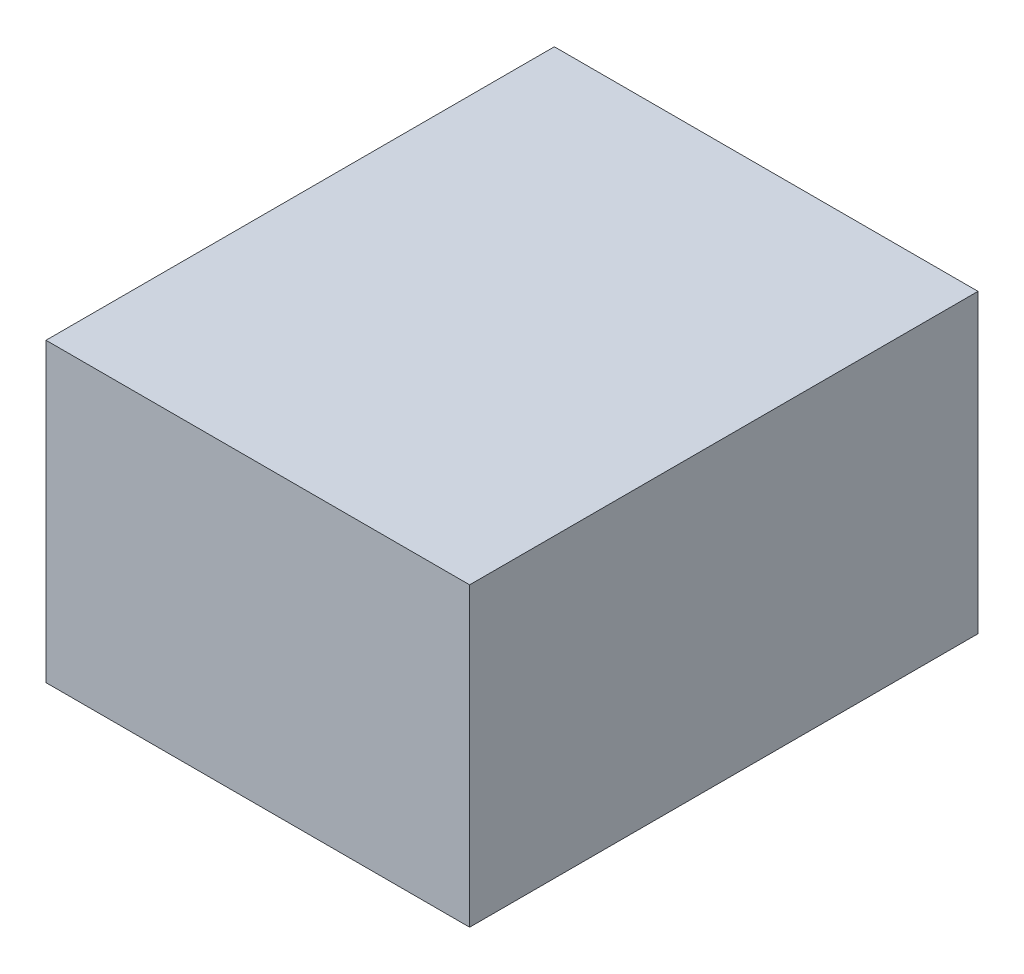
SolidWorks part; units mm, degrees
ref_plane "Front Plane" through (0, 0, 0) normal (0, 0, 1) x (1, 0, 0)
ref_plane "Top Plane" through (0, 0, 0) normal (0, 1, 0) x (1, 0, 0)
ref_plane "Right Plane" through (0, 0, 0) normal (1, 0, 0) x (0, 0, -1)
sketch "Sketch1" plane through (0, 0, 0) normal (0, 1, 0) x (1, 0, 0)
  line L1 (0, 0) -> (31.75, 0)
  line L2 (0, 0) -> (0, 38.1)
  line L3 (0, 38.1) -> (31.75, 38.1)
  line L4 (31.75, 0) -> (31.75, 38.1)
  dimension "D1" = 31.75
  dimension "D2" = 38.1
extrude "Boss-Extrude1" add sketch "Sketch1" along normal blind 22.225
sketch "Sketch4" plane through (31.75, 0, 0) normal (1, 0, 0) x (0, 0, -1)
  line L0 (0, 11.1125) -> (38.1, 11.1125) construction
  line L1 (0, 22.225) -> (0, 0) construction
  line L2 (38.1, 22.225) -> (38.1, 0) construction
  point P6 (19.05, 11.1125)
sketch "Sketch5" plane through (0, 0, 0) normal (-1, 0, 0) x (0, 0, 1)
  line L0 (-38.1, 11.1125) -> (0, 11.1125) construction
  line L1 (-38.1, 22.225) -> (-38.1, 0) construction
  line L2 (0, 22.225) -> (0, 0) construction
  point P6 (-19.05, 11.1125)
